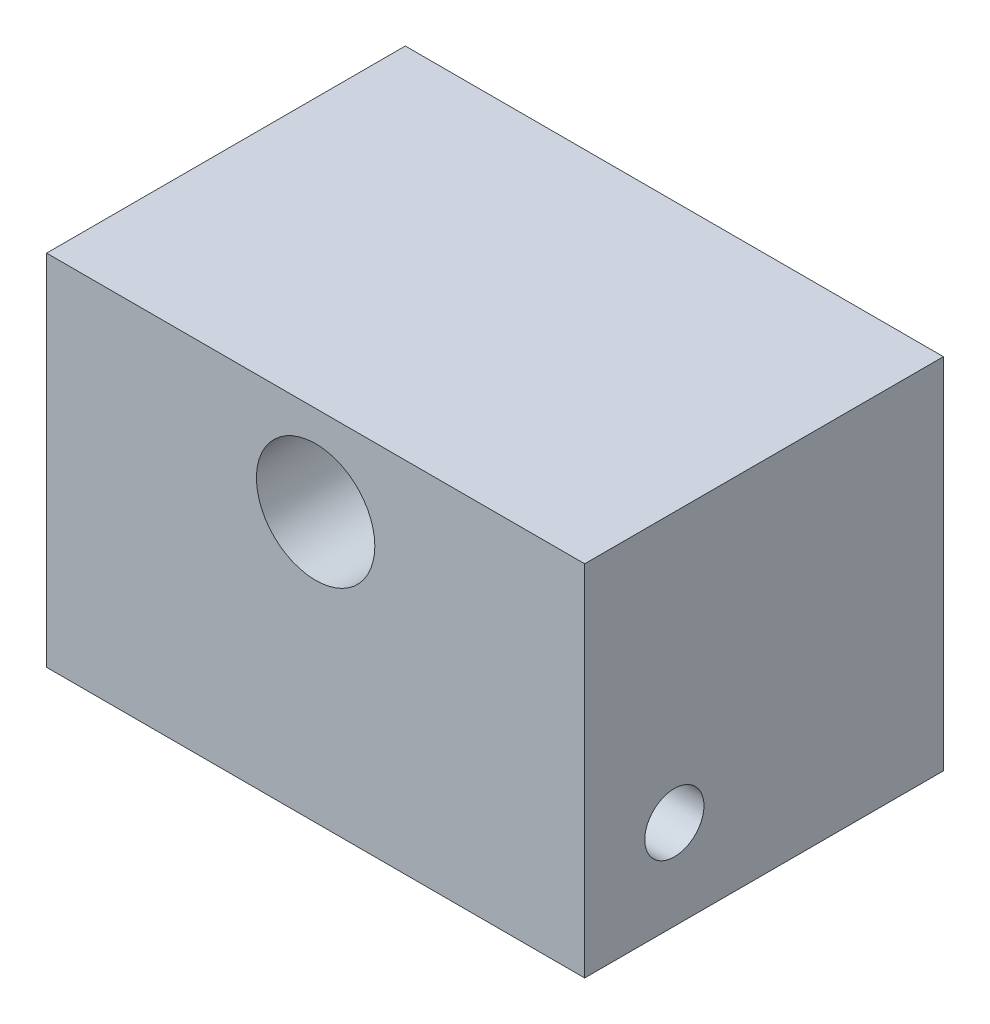
SolidWorks part; units mm, degrees
ref_plane "Ebene vorne" through (0, 0, 0) normal (0, 0, 1) x (1, 0, 0)
ref_plane "Ebene oben" through (0, 0, 0) normal (0, 1, 0) x (1, 0, 0)
ref_plane "Ebene rechts" through (0, 0, 0) normal (1, 0, 0) x (0, 0, -1)
sketch "Skizze1" plane through (0, 0, 0) normal (0, 0, 1) x (1, 0, 0)
  line L1 (0, 0) -> (30, 0)
  line L2 (0, 0) -> (0, 20)
  line L3 (0, 20) -> (30, 20)
  line L4 (30, 0) -> (30, 20)
  dimension "D1" = 30
  dimension "D2" = 20
extrude "Aufsatz-Linear austragen1" add sketch "Skizze1" along normal blind 20
hole_wizard "M6 Gewindebohrung" positions "Skizze6" profile "Skizze7" tap size "M4" standard "DIN"
sketch "Skizze6" plane through (0, 0, 0) normal (0, -1, 0) x (-1, 0, 0)
  line L7 (-30, -20) -> (-30, 0) construction
  line L9 (0, 0) -> (-30, 0) construction
  line L10 (0, -20) -> (0, 0) construction
  point P17 (-22.5, -7.5)
  point P25 (-7.5, -7.5)
  dimension "D1" = 7.5
  dimension "D2" = 7.5
  dimension "D3" = 7.5
  dimension "D4" = 7.5
sketch "Skizze7" plane through (22.5, 0, 7.5) normal (1, 0, 0) x (0, 0, -1)
  line L0 (0, 0) -> (0, 11.5)
  line L1 (0, 11.5) -> (1.65, 10.5086)
  line L2 (1.65, 10.5086) -> (1.65, 0)
  line L5 (1.65, 0) -> (0, 0)
  line L10 (0, 11.5) -> (-1.65, 10.5086) construction
  line L11 (0, -6.35) -> (0, 107.95) construction
  dimension "Bohrerdurchmesser" = 3.3
  dimension "Bohrungstiefe" = 11.5
  dimension "Spitzenwinkel" = 118
cosmetic thread "Bohrungsgewinde2"
cosmetic thread "Bohrungsgewinde4"
hole_wizard "Durchgangsloch für M61" positions "Skizze12" profile "Skizze11" hole size "M6" standard "DIN" end condition through all
sketch "Skizze12" plane through (0, 0, 20) normal (0, 0, 1) x (1, 0, 0)
  line L7 (0, 0) -> (30, 0) construction
  line L8 (30, 0) -> (30, 20) construction
  point P17 (15, 15)
  dimension "D1" = 15
  dimension "D2" = 15
sketch "Skizze11" plane through (15, 15, 20) normal (1, 0, 0) x (0, -1, 0)
  line L0 (0, 0) -> (0, 20)
  line L1 (0, 20) -> (3.3, 20)
  line L2 (3.3, 20) -> (3.3, 0)
  line L5 (3.3, 0) -> (0, 0)
  line L11 (0, -6.35) -> (0, 107.95) construction
  dimension "Bohrerdurchmesser" = 6.6
  dimension "Bohrungstiefe" = 20
hole_wizard "M4 Gewindebohrung1" positions "Skizze13" profile "Skizze14" tap size "M4" standard "DIN"
sketch "Skizze13" plane through (30, 0, 0) normal (1, 0, 0) x (0, 0, -1)
  line L0 (-20, 0) -> (-20, 20) construction
  line L2 (-20, 0) -> (0, 0) construction
  point P0 (-15, 5)
  dimension "D1" = 5
  dimension "D2" = 5
cosmetic thread "Bohrungsgewinde3"
sketch "Skizze14" plane through (30, 5, 15) normal (0, 1, 0) x (0, 0, -1)
  line L0 (0, 0) -> (0, 15)
  line L1 (0, 15) -> (1.65, 14.0086)
  line L2 (1.65, 14.0086) -> (1.65, 0)
  line L5 (1.65, 0) -> (0, 0)
  line L10 (0, 15) -> (-1.65, 14.0086) construction
  line L11 (0, -6.35) -> (0, 107.95) construction
  dimension "Bohrerdurchmesser" = 3.3
  dimension "Bohrungstiefe" = 15
  dimension "Spitzenwinkel" = 118
hole_wizard "M4 Gewindebohrung2" positions "Skizze15" profile "Skizze16" tap size "M4" standard "DIN"
sketch "Skizze15" plane through (0, 0, 0) normal (-1, 0, 0) x (0, 0, 1)
  line L0 (20, 20) -> (20, 0) construction
  line L1 (20, 0) -> (0, 0) construction
  point P0 (15, 5)
  dimension "D1" = 5
  dimension "D2" = 5
sketch "Skizze16" plane through (0, 5, 15) normal (0, 1, 0) x (0, 0, 1)
  line L0 (0, 0) -> (0, 15.9914)
  line L1 (0, 15.9914) -> (1.65, 15)
  line L2 (1.65, 15) -> (1.65, 0)
  line L5 (1.65, 0) -> (0, 0)
  line L10 (0, 15.9914) -> (-1.65, 15) construction
  line L11 (0, -6.35) -> (0, 107.95) construction
  dimension "Bohrerdurchmesser" = 3.3
  dimension "Bohrungstiefe" = 15
  dimension "Spitzenwinkel" = 118
cosmetic thread "Bohrungsgewinde5"
